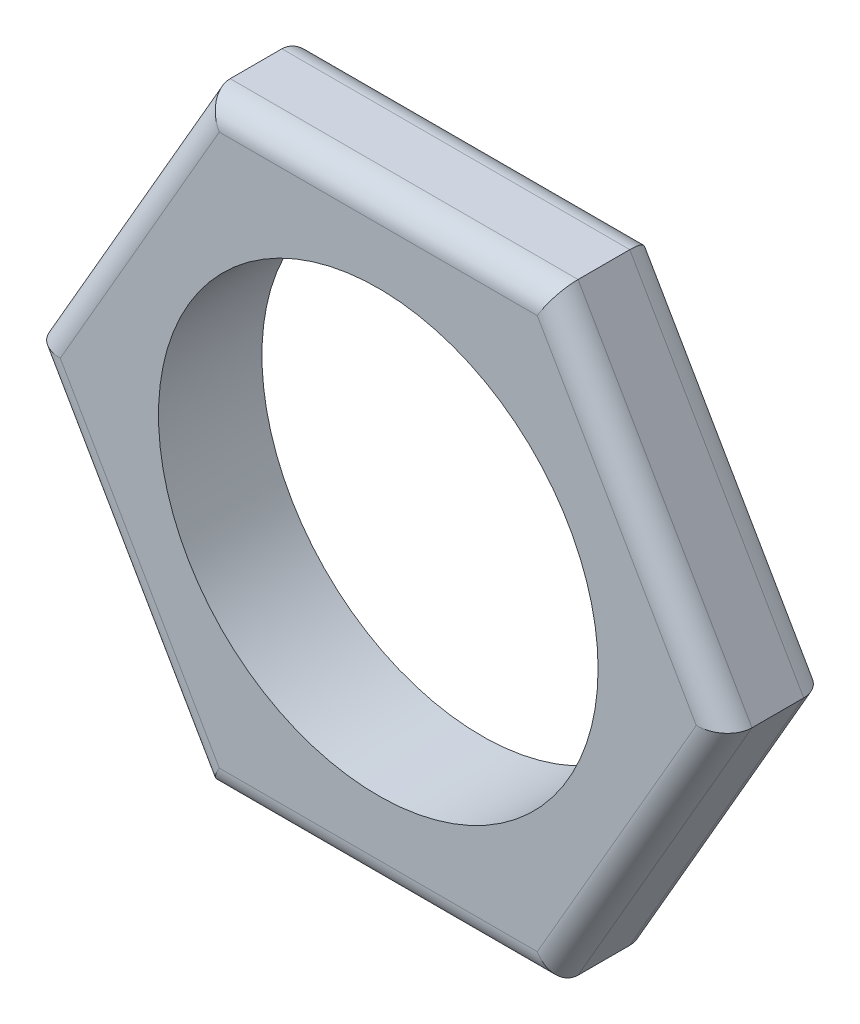
SolidWorks part; units mm, degrees
ref_plane "Front Plane" through (0, 0, 0) normal (0, 0, 1) x (1, 0, 0)
ref_plane "Top Plane" through (0, 0, 0) normal (0, 1, 0) x (1, 0, 0)
ref_plane "Right Plane" through (0, 0, 0) normal (1, 0, 0) x (0, 0, -1)
sketch "Sketch1" plane through (0, 0, 0) normal (0, 0, 1) x (1, 0, 0)
  line L0 (-5.1253, 2.9591) -> (-6.8337, 0)
  line L1 (5.1253, -2.9591) -> (3.4169, -5.9182)
  line L2 (0, 5.9182) -> (-3.4169, 5.9182)
  line L3 (0, 5.9182) -> (3.4169, 5.9182)
  line L4 (0, -5.9182) -> (-3.4169, -5.9182)
  line L5 (0, -5.9182) -> (3.4169, -5.9182)
  line L6 (-5.1253, 2.9591) -> (-3.4169, 5.9182)
  line L7 (5.1253, -2.9591) -> (6.8337, 0)
  line L8 (-5.1253, -2.9591) -> (-3.4169, -5.9182)
  line L9 (5.1253, 2.9591) -> (6.8337, 0)
  line L10 (-5.1253, -2.9591) -> (-6.8337, 0)
  line L11 (5.1253, 2.9591) -> (3.4169, 5.9182)
  circle A0 centre (0, 0) radius 4.318
extrude "Extrude1" add sketch "Sketch1" along normal blind 2.032
fillet "Fillet1" radius 0.508 12 edges at (5.1253, 2.9591, 0) (5.1253, -2.9591, 0) (0, -5.9182, 0) (-5.1253, -2.9591, 0) (-5.1253, 2.9591, 0) (0, 5.9182, 0) (-5.1253, 2.9591, 2.032) (-5.1253, -2.9591, 2.032) (0, -5.9182, 2.032) (5.1253, -2.9591, 2.032) (5.1253, 2.9591, 2.032) (0, 5.9182, 2.032)
